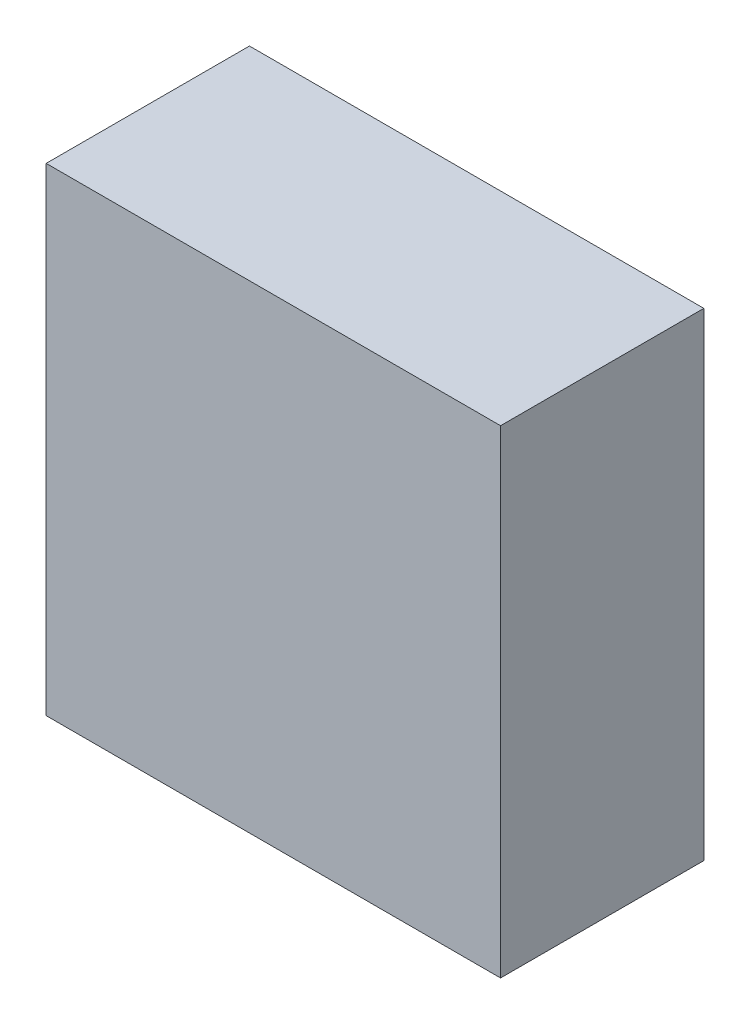
SolidWorks part; units mm, degrees
ref_plane "Front Plane" through (0, 0, 0) normal (0, 0, 1) x (1, 0, 0)
ref_plane "Top Plane" through (0, 0, 0) normal (0, 1, 0) x (1, 0, 0)
ref_plane "Right Plane" through (0, 0, 0) normal (1, 0, 0) x (0, 0, -1)
sketch "Sketch1" plane through (0, 0, 0) normal (0, 1, 0) x (1, 0, 0)
  line L1 (-14.478, 6.477) -> (14.478, 6.477)
  line L2 (-14.478, 6.477) -> (-14.478, -6.477)
  line L3 (-14.478, -6.477) -> (14.478, -6.477)
  line L4 (14.478, 6.477) -> (14.478, -6.477)
  line L5 (-14.478, 6.477) -> (14.478, -6.477) construction
  line L6 (-14.478, -6.477) -> (14.478, 6.477) construction
  point P0 (0, 0)
  dimension "D1" = 12.954
  dimension "D2" = 28.956
extrude "Boss-Extrude1" add sketch "Sketch1" along normal blind 30.48
sketch "Sketch2" plane through (14.478, 0, 0) normal (1, 0, 0) x (0, 0, -1)
  line L1 (-6.477, 22.86) -> (6.477, 22.86)
  line L2 (-6.477, 22.86) -> (-6.477, 19.812)
  line L3 (-6.477, 19.812) -> (6.477, 19.812)
  line L4 (6.477, 22.86) -> (6.477, 19.812)
  line L5 (-6.477, 22.86) -> (6.477, 19.812) construction
  line L6 (-6.477, 19.812) -> (6.477, 22.86) construction
  line L7 (0, 21.336) -> (0, 30.48) construction
  line L8 (-6.477, 30.48) -> (6.477, 30.48) construction
  line L9 (-6.477, 0) -> (6.477, 0) construction
  point P0 (0, 21.336)
  dimension "D1" = 19.812
  dimension "D2" = 3.048
